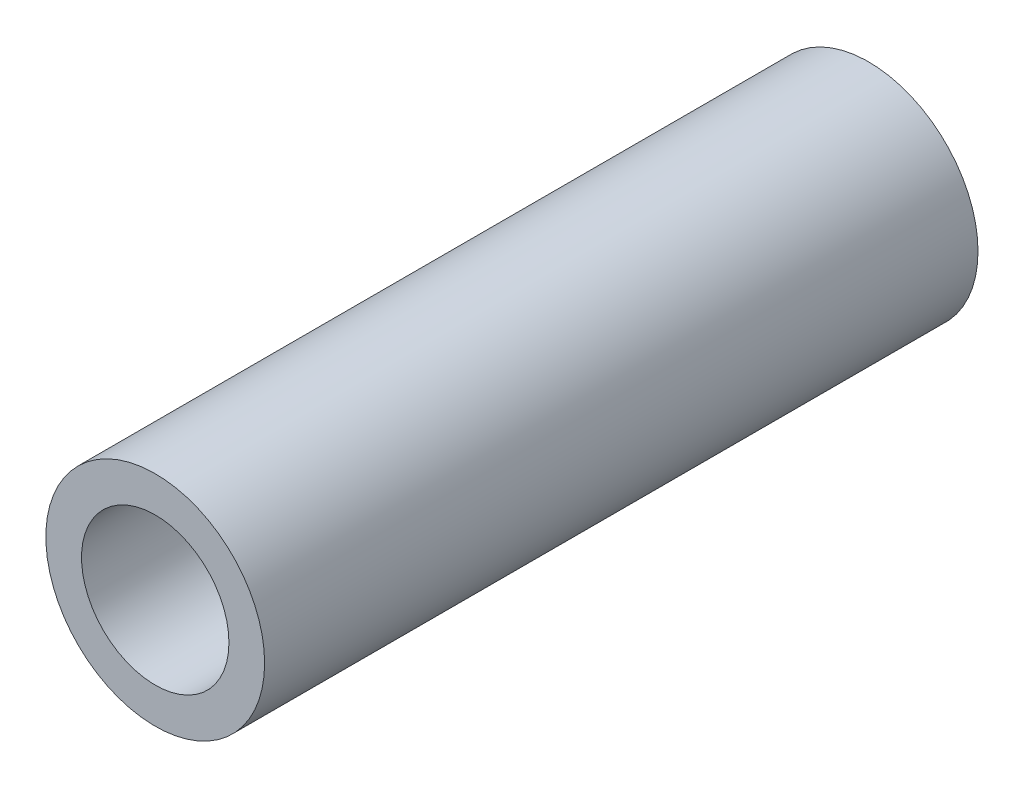
SolidWorks part; units mm, degrees
ref_plane "Front Plane" through (0, 0, 0) normal (0, 0, 1) x (1, 0, 0)
ref_plane "Top Plane" through (0, 0, 0) normal (0, 1, 0) x (1, 0, 0)
ref_plane "Right Plane" through (0, 0, 0) normal (1, 0, 0) x (0, 0, -1)
sketch "Sketch1" plane through (0, 0, 0) normal (0, 0, 1) x (1, 0, 0)
  circle A0 centre (0, 0) radius 1.55
  circle A1 centre (0, 0) radius 2.3
  dimension "D1" = 3.1
  dimension "D2" = 0.75
extrude "Boss-Extrude1" add sketch "Sketch1" along normal blind 15
